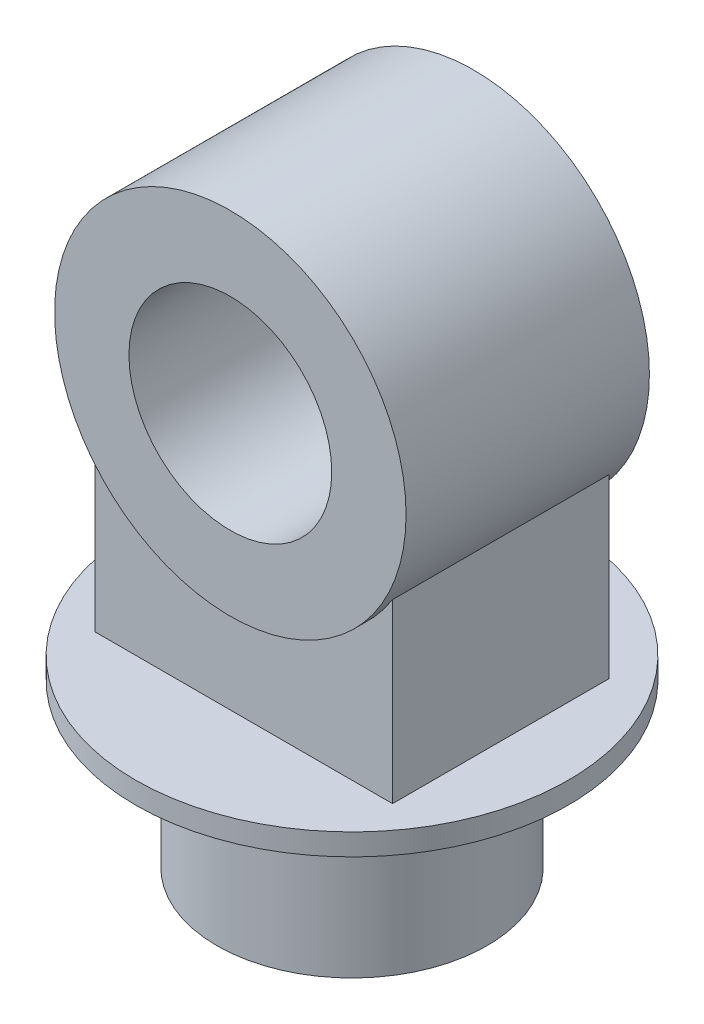
SolidWorks part; units mm, degrees
ref_plane "Front Plane" through (0, 0, 0) normal (0, 0, 1) x (1, 0, 0)
ref_plane "Top Plane" through (0, 0, 0) normal (0, 1, 0) x (1, 0, 0)
ref_plane "Right Plane" through (0, 0, 0) normal (1, 0, 0) x (0, 0, -1)
sketch "Sketch1" plane through (0, 0, 0) normal (0, 1, 0) x (1, 0, 0)
  circle A0 centre (0, 0) radius 100
  dimension "D1" = 200
extrude "Boss-Extrude1" add sketch "Sketch1" along normal blind 120
sketch "Sketch2" plane through (0, 120, 0) normal (0, 1, 0) x (1, 0, 0)
  circle A0 centre (0, 0) radius 160
  dimension "D1" = 320
extrude "Boss-Extrude2" add sketch "Sketch2" along normal blind 16
sketch "Sketch3" plane through (0, 0, 0) normal (0, 0, 1) x (1, 0, 0)
  line L0 (160, 136) -> (-160, 136) construction
  circle A0 centre (0, 336) radius 75
  circle A1 centre (0, 336) radius 130
  dimension "D1" = 150
  dimension "D2" = 260
  dimension "D3" = 200
extrude "Boss-Extrude3" add sketch "Sketch3" along normal mid plane 180 separate body
sketch "Sketch4" plane through (0, 136, 0) normal (0, 1, 0) x (1, 0, 0)
  line L1 (110, -80) -> (-110, -80)
  line L2 (110, -80) -> (110, 80)
  line L3 (110, 80) -> (-110, 80)
  line L4 (-110, -80) -> (-110, 80)
  line L5 (110, -80) -> (-110, 80) construction
  line L6 (110, 80) -> (-110, -80) construction
  point P0 (0, 0)
  dimension "D1" = 160
  dimension "D2" = 220
extrude "Boss-Extrude4" add sketch "Sketch4" along normal up to next
